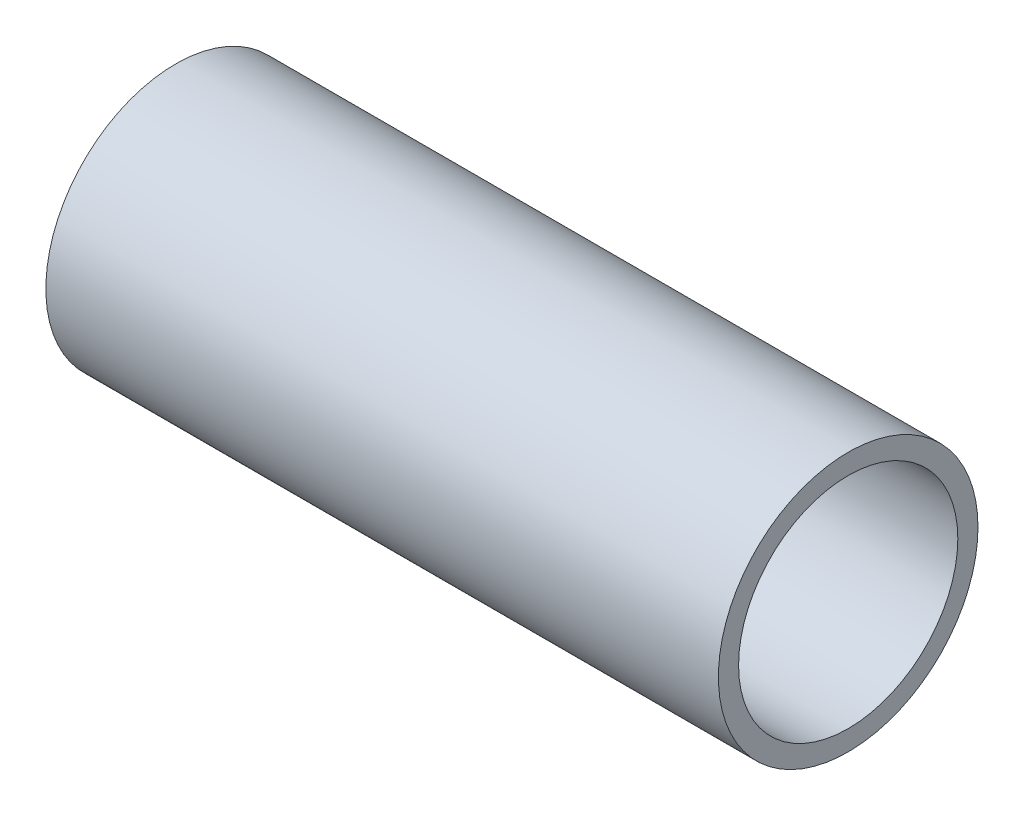
SolidWorks part; units mm, degrees
ref_plane "Alzado" through (0, 0, 0) normal (0, 0, 1) x (1, 0, 0)
ref_plane "Planta" through (0, 0, 0) normal (0, 1, 0) x (1, 0, 0)
ref_plane "Vista lateral" through (0, 0, 0) normal (1, 0, 0) x (0, 0, -1)
sketch "Croquis1" plane through (0, 0, 0) normal (1, 0, 0) x (0, 0, -1)
  circle A0 centre (0, 0) radius 9.65
  circle A1 centre (0, 0) radius 8.15
  dimension "D1" = 19.3
  dimension "D2" = 1.5
extrude "Saliente-Extruir1" add sketch "Croquis1" against normal blind 50
